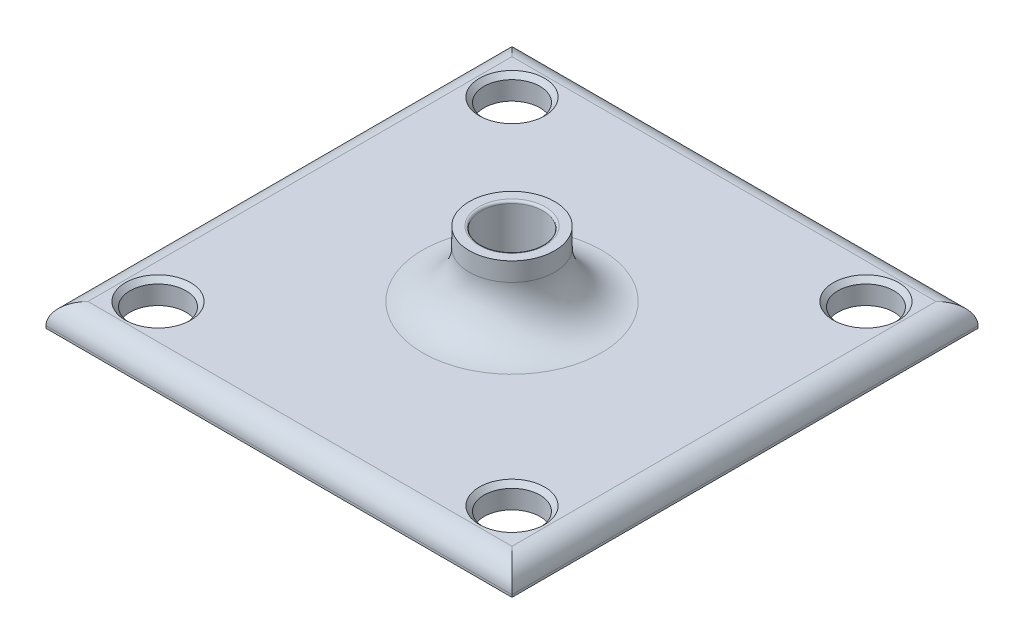
SolidWorks part; units mm, degrees
ref_plane "Front Plane" through (0, 0, 0) normal (0, 0, 1) x (1, 0, 0)
ref_plane "Top Plane" through (0, 0, 0) normal (0, 1, 0) x (1, 0, 0)
ref_plane "Right Plane" through (0, 0, 0) normal (1, 0, 0) x (0, 0, -1)
sketch "Sketch1" plane through (0, 0, 0) normal (0, 1, 0) x (1, 0, 0)
  line L1 (-25, -25) -> (25, -25)
  line L2 (-25, -25) -> (-25, 25)
  line L3 (-25, 25) -> (25, 25)
  line L4 (25, -25) -> (25, 25)
  line L5 (-25, -25) -> (25, 25) construction
  line L6 (-25, 25) -> (25, -25) construction
  point P0 (0, 0)
  dimension "D1" = 50
  dimension "D2" = 50
extrude "Boss-Extrude1" add sketch "Sketch1" along normal blind 2.5
sketch "Sketch2" plane through (0, 2.5, 0) normal (0, 1, 0) x (1, 0, 0)
  circle A0 centre (0, 0) radius 1.525
extrude "Cut-Extrude1" cut sketch "Sketch2" against normal blind 97.5
sketch "Sketch6" plane through (0, 2.5, 0) normal (0, 1, 0) x (1, 0, 0)
  line L0 (-25, 25) -> (-18.9896, 18.9896)
  line L1 (0, 25) -> (0, 21.2334)
  line L2 (25, 25) -> (-25, 25) construction
  line L3 (0, -1.375) -> (0, 1.375) construction
  line L4 (0, 21.2334) -> (0, 0)
  line L5 (0, 0) -> (-5.9944, 0)
  line L6 (-1.375, 0) -> (1.375, 0) construction
  circle A0 centre (-18.9896, 18.9896) radius 3
  circle A1 centre (18.9896, 18.9896) radius 3
  circle A2 centre (18.9896, -18.9896) radius 3
  circle A3 centre (-18.9896, -18.9896) radius 3
  dimension "D1" = 8.5
extrude "Cut-Extrude2" cut sketch "Sketch6" against normal blind 97.5
sketch "Sketch7" plane through (0, 2.5, 0) normal (0, 1, 0) x (1, 0, 0)
  circle A0 centre (0, 0) radius 3.325
  circle A1 centre (0, 0) radius 4.575
  dimension "D1" = 6.65
  dimension "D2" = 9.15
extrude "Boss-Extrude2" add sketch "Sketch7" along normal blind 7
fillet "Fillet1" radius 5 1 edges at (0, 2.5, -4.575)
fillet "Fillet2" radius 2.25 4 edges at (0, 2.5, -25) (25, 2.5, 0) (0, 2.5, 25) (-25, 2.5, 0)
chamfer "Chamfer1" distance 0.5 angle 45 4 edges at (-18.9896, 2.5, 21.9896) (18.9896, 2.5, 21.9896) (18.9896, 2.5, -15.9896) (-18.9896, 2.5, -15.9896)
fillet "Fillet3" radius 0.25 1 edges at (0, 9.5, 3.325)
